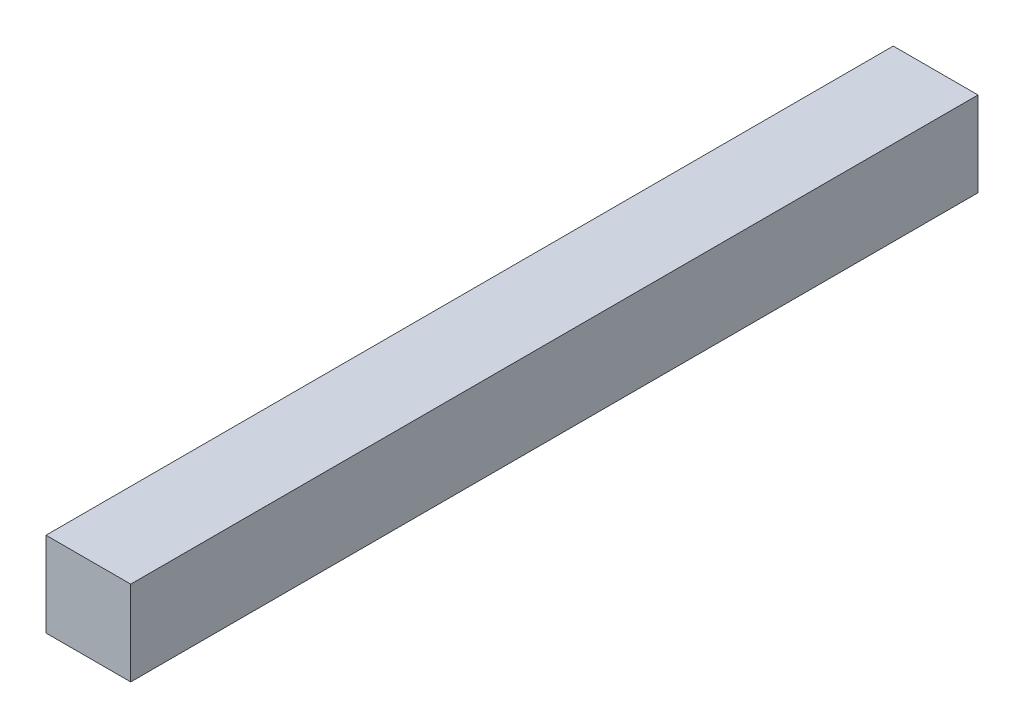
SolidWorks part; units mm, degrees
ref_plane "Front" through (0, 0, 0) normal (0, 0, 1) x (1, 0, 0)
ref_plane "Top" through (0, 0, 0) normal (0, 1, 0) x (1, 0, 0)
ref_plane "Right" through (0, 0, 0) normal (1, 0, 0) x (0, 0, -1)
other "Configuration Table"
sketch "Sketch1" plane through (0, 0, 0) normal (0, 0, 1) x (1, 0, 0)
  line L1 (0, 0) -> (1000, 0)
  line L2 (0, 0) -> (0, 1000)
  line L3 (0, 1000) -> (1000, 1000)
  line L4 (1000, 0) -> (1000, 1000)
  dimension "D1" = 1000
  dimension "D2" = 1000
extrude "Extrude1" add sketch "Sketch1" along normal blind 10000
